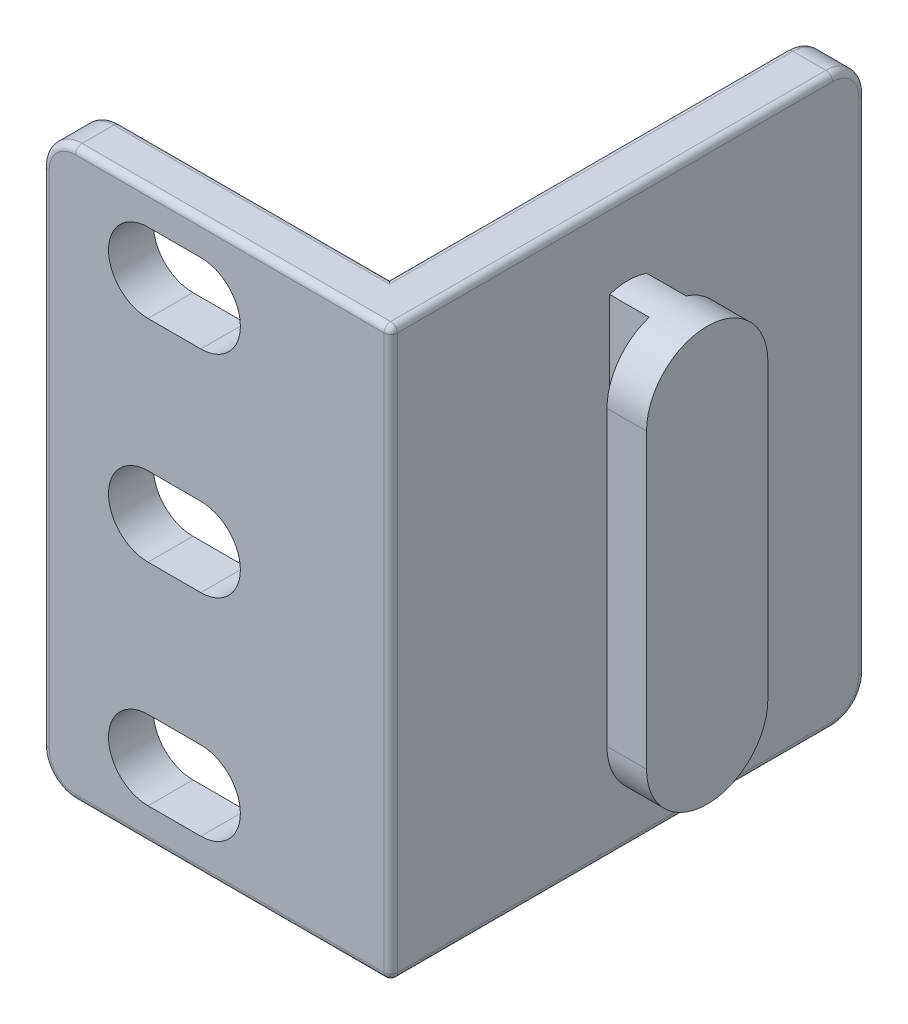
SolidWorks part; units mm, degrees
material "ABS_Black"
ref_plane "Přední rovina" through (0, 0, 0) normal (0, 0, 1) x (1, 0, 0)
ref_plane "Horní rovina" through (0, 0, 0) normal (0, 1, 0) x (1, 0, 0)
ref_plane "Pravá rovina" through (0, 0, 0) normal (1, 0, 0) x (0, 0, -1)
sketch "Skica2" plane through (0, 0, 0) normal (0, 1, 0) x (1, 0, 0)
  line L6 (0, 0) -> (-26.4, 0)
  line L7 (-26.4, 0) -> (-26.4, 3.4)
  line L8 (-26.4, 3.4) -> (-3.5, 3.4)
  line L9 (-3.5, 3.4) -> (-3.5, 36)
  line L10 (-3.5, 36) -> (0, 36)
  line L11 (0, 36) -> (0, 0)
  dimension "D1" = 26.4
  dimension "D2" = 36
  dimension "D3" = 3.4
  dimension "D4" = 3.5
extrude "Přidat vysunutím1" add sketch "Skica2" along normal mid plane 43
sketch "Skica3" plane through (0, 0, 0) normal (1, 0, 0) x (0, 0, -1)
  line L0 (0, 0) -> (36, 0) construction
  line L1 (36, 21.5) -> (36, -21.5) construction
  line L2 (18, 21.5) -> (18, -21.5) construction
  line L3 (0, 21.5) -> (36, 21.5) construction
  line L4 (0, -21.5) -> (36, -21.5) construction
  line L5 (16.6, 15.4818) -> (16.6, -15.4818)
  line L6 (19.4, 15.4818) -> (19.4, -15.4818)
  arc A0 (19.4, 15.4818) -> (16.6, 15.4818) centre (18, 11.1) ccw
  arc A1 (16.6, -15.4818) -> (19.4, -15.4818) centre (18, -11.1) ccw
  dimension "D1" = 22.2
  dimension "D4" = 4.6
  dimension "D5" = 4.6
  dimension "D2" = 11.1
  dimension "D3" = 2.8
extrude "Přidat vysunutím2" add sketch "Skica3" along normal blind 3
sketch "Skica4" plane through (3, 0, 0) normal (1, 0, 0) x (0, 0, -1)
  line L0 (13.4, -11.1) -> (13.4, 11.1)
  line L1 (22.6, 11.1) -> (22.6, -11.1)
  arc A0 (22.6, 11.1) -> (13.4, 11.1) centre (18, 11.1) ccw
  arc A1 (13.4, -11.1) -> (22.6, -11.1) centre (18, -11.1) ccw
extrude "Přidat vysunutím3" add sketch "Skica4" along normal blind 3
sketch "Skica5" plane through (0, 0, 0) normal (0, 0, 1) x (1, 0, 0)
  line L0 (0, 0) -> (-26.4, 0) construction
  line L1 (-26.4, 21.5) -> (-26.4, -21.5) construction
  line L2 (-16.4, 20.0642) -> (-16.4, -20.0642) construction
  line L3 (-14.4002, 0) -> (-18.3998, 0) construction
  line L4 (-14.4002, 16) -> (-18.3998, 16) construction
  line L5 (-14.4002, -3) -> (-18.3998, -3)
  line L6 (-14.4002, 3) -> (-18.3998, 3)
  line L7 (-14.4002, 13) -> (-18.3998, 13)
  line L8 (-14.4002, 19) -> (-18.3998, 19)
  line L9 (-14.4002, -16) -> (-18.3998, -16) construction
  line L10 (-14.4002, -19) -> (-18.3998, -19)
  line L11 (-14.4002, -13) -> (-18.3998, -13)
  arc A0 (-14.4002, -3) -> (-14.4002, 3) centre (-14.4002, 0) ccw
  arc A1 (-18.3998, 3) -> (-18.3998, -3) centre (-18.3998, 0) ccw
  arc A2 (-14.4002, 13) -> (-14.4002, 19) centre (-14.4002, 16) ccw
  arc A3 (-18.3998, 19) -> (-18.3998, 13) centre (-18.3998, 16) ccw
  arc A4 (-14.4002, -19) -> (-14.4002, -13) centre (-14.4002, -16) ccw
  arc A5 (-18.3998, -13) -> (-18.3998, -19) centre (-18.3998, -16) ccw
  point P11 (-16.4, 0)
  point P17 (-16.4, 16)
  point P25 (-16.4, -16)
  dimension "D1" = 10
  dimension "D2" = 2
  dimension "D3" = 2
extrude "Odebrat vysunutím1" cut sketch "Skica5" against normal through all
fillet "Zaoblit1" radius 2.5 4 edges at (-26.4, -21.5, -1.7) (-26.4, 21.5, -1.7) (-1.75, -21.5, -36) (-1.75, 21.5, -36)
fillet "Zaoblit2" radius 0.5 21 edges at (-13.7, 21.5, -3.4) (-25.6678, 20.7678, -3.4) (-26.4, 0, -3.4) (-25.6678, -20.7678, -3.4) (-3.5, 21.5, -18.45) (-3.5, 20.7678, -35.2678) (-3.5, -21.5, -18.45) (-3.5, -20.7678, -35.2678) (0, -21.5, -16.75) (0, -20.7678, -35.2678) (0, 0, -36) (0, 20.7678, -35.2678) (-11.95, 21.5, 0) (-25.6678, 20.7678, 0) (-11.95, -21.5, 0) (-25.6678, -20.7678, 0) (-13.7, -21.5, -3.4) (-3.5, 0, -36) (0, 21.5, -16.75) (0, 0, 0) (-26.4, 0, 0)
